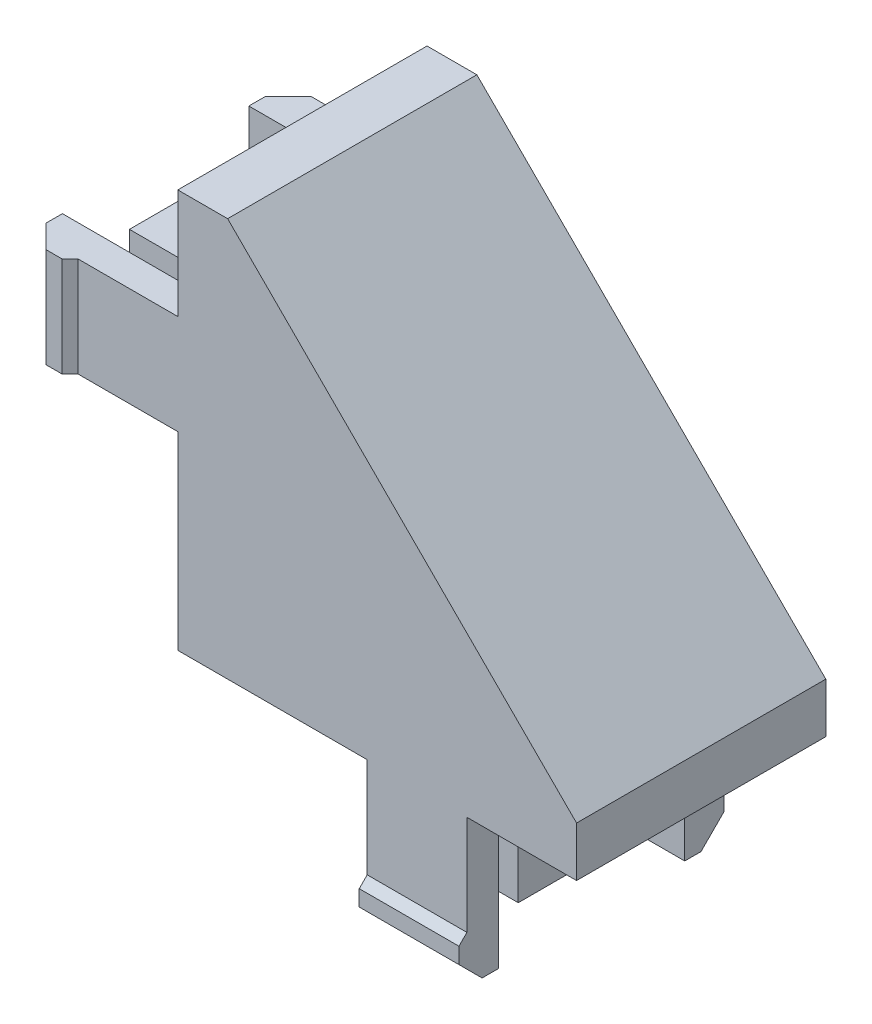
SolidWorks part; units mm, degrees
ref_plane "Front Plane" through (0, 0, 0) normal (0, 0, 1) x (1, 0, 0)
ref_plane "Top Plane" through (0, 0, 0) normal (0, 1, 0) x (1, 0, 0)
ref_plane "Right Plane" through (0, 0, 0) normal (1, 0, 0) x (0, 0, -1)
sketch "Sketch1" plane through (0, 0, 0) normal (0, 0, 1) x (1, 0, 0)
  line L0 (0, 0) -> (0, 25.4)
  line L1 (0, 25.4) -> (3.175, 25.4)
  line L2 (3.175, 25.4) -> (25.4, 3.175)
  line L3 (25.4, 3.175) -> (25.4, 0)
  line L4 (25.4, 0) -> (0, 0)
  dimension "D1" = 25.4
  dimension "D2" = 25.4
  dimension "D3" = 3.175
  dimension "D4" = 3.175
extrude "Boss-Extrude1" add sketch "Sketch1" along normal blind 15.875
sketch "Sketch2" plane through (0, 0, 0) normal (-1, 0, 0) x (0, 0, 1)
  line L0 (0, 25.4) -> (0, 0) construction
  line L1 (0, 18.415) -> (15.875, 18.415)
  line L2 (0, 18.415) -> (0, 12.065)
  line L3 (0, 12.065) -> (15.875, 12.065)
  line L4 (15.875, 18.415) -> (15.875, 12.065)
  line L7 (15.875, 0) -> (0, 0) construction
  line L8 (15.875, 25.4) -> (15.875, 0) construction
  dimension "D1" = 12.065
  dimension "D2" = 6.35
extrude "Boss-Extrude2" add sketch "Sketch2" along normal blind 6.35
sketch "Sketch3" plane through (0, 18.415, 0) normal (0, 1, 0) x (1, 0, 0)
  line L0 (-9.35, -14.907) -> (-9.35, -13.875)
  line L5 (-9.35, -13.875) -> (-6.35, -13.875)
  line L6 (-6.35, -13.875) -> (-6.35, -15.875)
  line L7 (-6.35, -15.875) -> (-6.858, -16.383)
  line L8 (-6.858, -16.383) -> (-7.874, -16.383)
  line L9 (-7.874, -16.383) -> (-9.35, -14.907)
  line L10 (-7.366, -16.891) -> (-7.874, -16.383) construction
  line L11 (-6.858, -16.383) -> (-7.366, -16.891) construction
  line L12 (-6.35, -15.875) -> (-6.35, 0) construction
  line L13 (-6.35, -7.9375) -> (-9.35, -7.9375) construction
  line L14 (-7.874, 0.508) -> (-9.35, -0.968)
  line L15 (-6.858, 0.508) -> (-7.874, 0.508)
  line L16 (-6.35, 0) -> (-6.858, 0.508)
  line L17 (-6.35, -2) -> (-6.35, 0)
  line L18 (-9.35, -2) -> (-6.35, -2)
  line L19 (-9.35, -0.968) -> (-9.35, -2)
  dimension "D1" = 3
  dimension "D2" = 0.508
  dimension "D3" = 135
  dimension "D4" = 2
  dimension "D5" = 1.032
extrude "Boss-Extrude3" add sketch "Sketch3" against normal blind 6.35
sketch "Sketch4" plane through (0, 18.415, 0) normal (0, 1, 0) x (1, 0, 0)
  line L0 (0, -15.875) -> (0, 0) construction
  line L1 (-6.35, -13.875) -> (0, -13.875)
  line L2 (-6.35, -13.875) -> (-6.35, -12.605)
  line L3 (-6.35, -12.605) -> (0, -12.605)
  line L4 (0, -13.875) -> (0, -12.605)
  line L5 (-6.35, -7.9375) -> (0, -7.9375) construction
  line L6 (-6.35, -13.875) -> (-6.35, -2) construction
  line L7 (-6.35, -3.27) -> (0, -3.27)
  line L8 (0, -2) -> (0, -3.27)
  line L9 (-6.35, -2) -> (0, -2)
  line L10 (-6.35, -2) -> (-6.35, -3.27)
  dimension "D1" = 1.27
extrude "Cut-Extrude1" cut sketch "Sketch4" against normal blind 6.35
ref_plane "Plane1" through (0, 0, 0) normal (0.7071, -0.7071, 0) x (0, 0, -1)
mirror "Mirror1" about plane through (0, 0, 0) normal (0.7071, -0.7071, 0) of "Cut-Extrude1", "Boss-Extrude3", "Boss-Extrude2"
